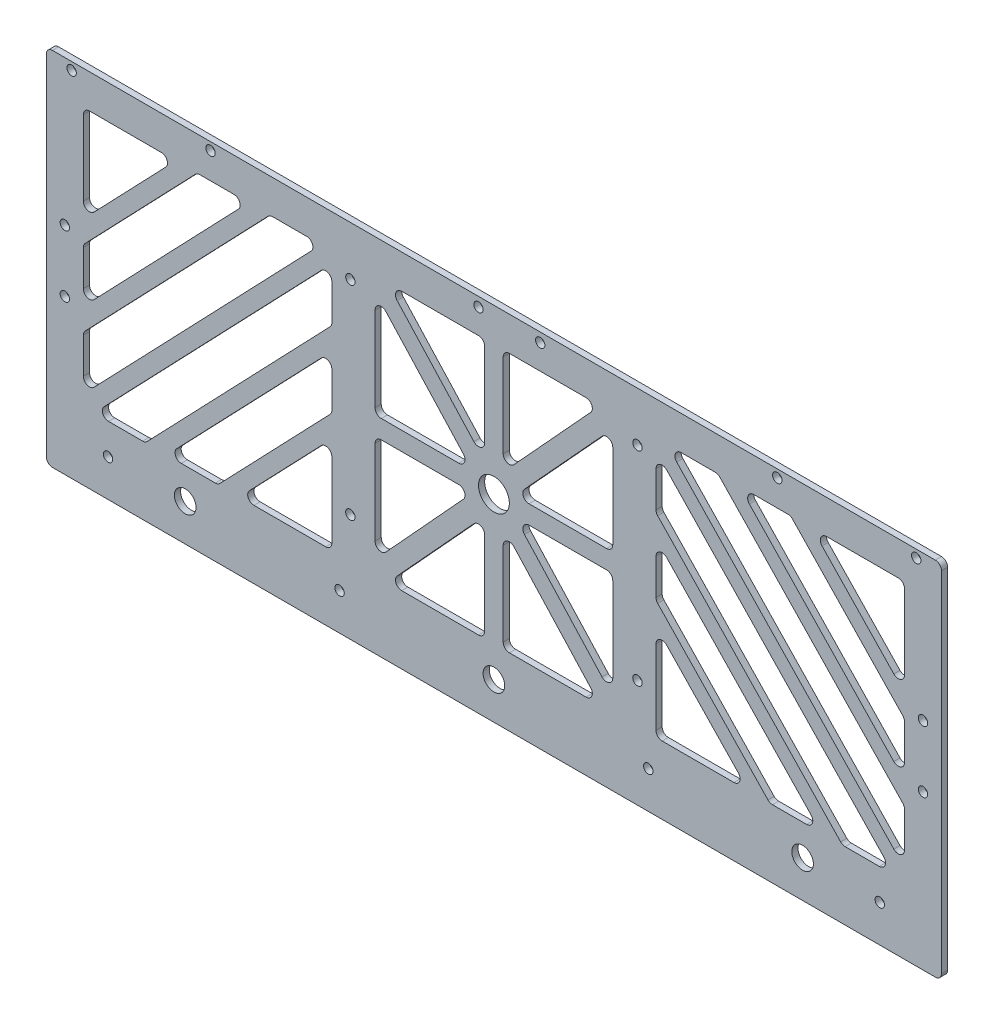
SolidWorks part; units mm, degrees
material "Thornel Mat VMA"
ref_plane "前视基准面" through (0, 0, 0) normal (0, 0, 1) x (1, 0, 0)
ref_plane "上视基准面" through (0, 0, 0) normal (0, 1, 0) x (1, 0, 0)
ref_plane "右视基准面" through (0, 0, 0) normal (1, 0, 0) x (0, 0, -1)
sketch "草图1" plane through (0, 0, 0) normal (0, 0, 1) x (1, 0, 0)
  line L1 (-145, -58.5) -> (145, -58.5)
  line L2 (-145, -58.5) -> (-145, 58.5)
  line L3 (-145, 58.5) -> (145, 58.5)
  line L4 (145, -58.5) -> (145, 58.5)
  line L5 (0, 58.5) -> (0, -58.5) construction
  line L6 (-145, 0) -> (145, 0) construction
  point P0 (0, 0)
  dimension "D1" = 290
  dimension "D2" = 117
extrude "凸台-拉伸1" add sketch "草图1" along normal mid plane 2
sketch "草图2" plane through (0, 0, -1) normal (0, 0, -1) x (-1, 0, 0)
  circle A0 centre (136.8, 56) radius 1.25 construction
  circle A1 centre (91.8, 56) radius 1.25 construction
  circle A2 centre (136.8, 56) radius 1.25 construction
  circle A3 centre (91.8, 56) radius 1.25 construction
  circle A4 centre (91.8, 56) radius 1.525
  circle A5 centre (136.8, 56) radius 1.525
  dimension "D1" = 3.05
extrude "切除-拉伸1" cut sketch "草图2" against normal blind 10
mirror "镜向1" about plane through (0, 0, 0) normal (1, 0, 0) of "切除-拉伸1"
sketch "草图3" plane through (0, 0, -1) normal (0, 0, -1) x (-1, 0, 0)
  circle A0 centre (100, -46.5) radius 3.5 construction
  circle A1 centre (0, -46.5) radius 3.5 construction
  circle A2 centre (-100, -46.5) radius 3.5 construction
  circle A3 centre (100, -46.5) radius 3.5
  circle A4 centre (0, -46.5) radius 3.5
  circle A5 centre (-100, -46.5) radius 3.5
extrude "切除-拉伸2" cut sketch "草图3" against normal blind 10
sketch "草图4" plane through (0, 0, -1) normal (0, 0, -1) x (-1, 0, 0)
  line L0 (-100, -46.5) -> (0, -46.5) construction
  line L1 (0, -46.5) -> (100, -46.5) construction
  line L2 (-100, -46.5) -> (-125, -46.5) construction
  line L3 (100, -46.5) -> (125, -46.5) construction
  circle A0 centre (-50, -46.5) radius 1.525
  circle A1 centre (50, -46.5) radius 1.525
  circle A2 centre (-125, -46.5) radius 1.525
  circle A3 centre (125, -46.5) radius 1.525
  dimension "D3" = 3.05
  dimension "D1" = 25
  dimension "D2" = 25
extrude "切除-拉伸3" cut sketch "草图4" against normal blind 10
sketch "草图5" plane through (0, 0, -1) normal (0, 0, -1) x (-1, 0, 0)
  circle A0 centre (139, -8.5) radius 1.25 construction
  circle A1 centre (139, 11.5) radius 1.25 construction
  circle A2 centre (139, -8.5) radius 1.25 construction
  circle A3 centre (139, 11.5) radius 1.25 construction
  circle A4 centre (139, 11.5) radius 1.525
  circle A5 centre (139, -8.5) radius 1.525
  dimension "D1" = 3.05
extrude "切除-拉伸4" cut sketch "草图5" against normal blind 10
mirror "镜向2" about plane through (0, 0, 0) normal (1, 0, 0) of "切除-拉伸4"
fillet "圆角1" radius 2 4 edges at (145, -58.5, 0) (-145, -58.5, 0) (-145, 58.5, 0) (145, 58.5, 0)
sketch "草图6" plane through (0, 0, -1) normal (0, 0, -1) x (-1, 0, 0)
  circle A0 centre (5, 55.5) radius 1.25 construction
  circle A1 centre (-15, 55.5) radius 1.25 construction
  circle A2 centre (5, 55.5) radius 1.25 construction
  circle A3 centre (-15, 55.5) radius 1.25 construction
  circle A4 centre (-15, 55.5) radius 1.5
  circle A5 centre (5, 55.5) radius 1.5
  dimension "D1" = 3
extrude "切除-拉伸5" cut sketch "草图6" against normal blind 10
sketch "草图7" plane through (0, 0, -1) normal (0, 0, -1) x (-1, 0, 0)
  circle A0 centre (-46.5, 42.5) radius 1.25 construction
  circle A1 centre (-46.5, -23.5) radius 1.25 construction
  circle A2 centre (-46.5, 42.5) radius 1.25 construction
  circle A3 centre (-46.5, -23.5) radius 1.25 construction
  circle A4 centre (-46.5, 42.5) radius 1.525
  circle A5 centre (-46.5, -23.5) radius 1.525
  dimension "D1" = 3.05
extrude "切除-拉伸6" cut sketch "草图7" against normal blind 10
mirror "镜向3" about plane through (0, 0, 0) normal (1, 0, 0) of "切除-拉伸6"
sketch "草图8" plane through (0, 0, -1) normal (0, 0, -1) x (-1, 0, 0)
  line L0 (-38.5, 47.5) -> (-38.5, -36.5)
  line L1 (-38.5, -36.5) -> (38.5, -36.5)
  line L2 (38.5, -36.5) -> (38.5, 47.5)
  line L3 (38.5, 47.5) -> (-38.5, 47.5)
  line L4 (0, 47.5) -> (0, -36.5) construction
  line L5 (-38.5, 47.5) -> (38.5, -36.5) construction
  line L6 (38.5, 47.5) -> (-38.5, -36.5) construction
  line L7 (-38.5, 5.5) -> (38.5, 5.5) construction
  line L8 (-40.7115, 45.4728) -> (36.2885, -38.5272)
  line L9 (-3, 47.5) -> (-3, -36.5)
  line L10 (36.2885, 49.5272) -> (-40.7115, -34.4728)
  line L11 (-38.5, 2.5) -> (38.5, 2.5)
  line L12 (-36.2885, 49.5272) -> (40.7115, -34.4728)
  line L13 (3, 47.5) -> (3, -36.5)
  line L14 (40.7115, 45.4728) -> (-36.2885, -38.5272)
  line L15 (-38.5, 8.5) -> (38.5, 8.5)
  circle A0 centre (0, -46.5) radius 3.5 construction
  circle A1 centre (-46.5, 42.5) radius 1.525 construction
  circle A2 centre (5, 55.5) radius 1.5 construction
  dimension "D2" = 8
  dimension "D1" = 10
  dimension "D3" = 8
  dimension "D4" = 3
  dimension "D5" = 3
extrude "切除-拉伸7" cut sketch "草图8" against normal blind 10 contours L8 L13 L1 | L9 L14 L1 | L11 L0 L10 | L0 L15 L8 | L3 L12 L9 | L3 L13 L10 | L14 L15 L2 | L11 L12 L2
fillet "圆角2" radius 2 24 edges at (-38.5, 2.5, 0) (-38.5, -32.0603, 0) (-6.8197, 2.5, 0) (-3, 13.2124, 0) (-3, 47.5, 0) (-34.4303, 47.5, 0) (-38.5, 8.5, 0) (-6.8197, 8.5, 0) (-38.5, 43.0603, 0) (6.8197, 8.5, 0) (38.5, 8.5, 0) (38.5, 43.0603, 0) (3, 13.2124, 0) (34.4303, 47.5, 0) (3, 47.5, 0) (6.8197, 2.5, 0) (38.5, -32.0603, 0) (38.5, 2.5, 0) (-34.4303, -36.5, 0) (-3, -36.5, 0) (-3, -2.2124, 0) (3, -2.2124, 0) (3, -36.5, 0) (34.4303, -36.5, 0)
sketch "草图9" plane through (0, 0, -1) normal (0, 0, -1) x (-1, 0, 0)
  line L0 (23.9331, 8.5) -> (23.9331, 2.5) construction
  line L1 (11.3662, 8.5) -> (36.5, 8.5) construction
  line L2 (11.3662, 2.5) -> (36.5, 2.5) construction
  line L3 (0, 5.5) -> (23.9331, 5.5) construction
  line L4 (0, 5.5) -> (0, 0) construction
  circle A0 centre (0, 5.5) radius 5
  dimension "D1" = 10
extrude "切除-拉伸8" cut sketch "草图9" against normal blind 10
sketch "草图10" plane through (0, 0, -1) normal (0, 0, -1) x (-1, 0, 0)
  line L0 (-5, 47.5) -> (-29.8838, 47.5) construction
  line L1 (-133, 47.5) -> (-52.5, 47.5)
  line L2 (-133, 47.5) -> (-133, -36.5)
  line L3 (-133, -36.5) -> (-52.5, -36.5)
  line L4 (-52.5, 47.5) -> (-52.5, -36.5)
  line L5 (-52.5, -5.2529) -> (-82.4452, -36.5)
  line L6 (-29.8838, -36.5) -> (-5, -36.5) construction
  line L7 (-133, -36.5) -> (-52.5, 47.5) construction
  line L8 (-129.5373, -36.5) -> (-52.5, 43.8868)
  line L9 (-133, -32.8868) -> (-55.9627, 47.5)
  line L10 (-112.9166, -36.5) -> (-52.5, 26.5434)
  line L11 (-52.5, 19.317) -> (-105.9912, -36.5)
  line L12 (-52.5, 1.9735) -> (-89.3705, -36.5)
  line L13 (-103.0548, 47.5) -> (-133, 16.2529)
  line L14 (-96.1295, 47.5) -> (-133, 9.0265)
  line L15 (-133, -15.5434) -> (-72.5834, 47.5)
  line L16 (-79.5088, 47.5) -> (-133, -8.317)
  line L17 (0, 0) -> (0, 58.5) construction
  line L18 (-143, 58.5) -> (143, 58.5) construction
  line L19 (133, -36.5) -> (52.5, 47.5) construction
  line L20 (79.5088, 47.5) -> (133, -8.317)
  line L21 (133, -15.5434) -> (72.5834, 47.5)
  line L22 (96.1295, 47.5) -> (133, 9.0265)
  line L23 (103.0548, 47.5) -> (133, 16.2529)
  line L24 (52.5, 1.9735) -> (89.3705, -36.5)
  line L25 (52.5, 19.317) -> (105.9912, -36.5)
  line L26 (112.9166, -36.5) -> (52.5, 26.5434)
  line L27 (133, -32.8868) -> (55.9627, 47.5)
  line L28 (129.5373, -36.5) -> (52.5, 43.8868)
  line L29 (52.5, -5.2529) -> (82.4452, -36.5)
  line L30 (52.5, 47.5) -> (52.5, -36.5)
  line L31 (133, -36.5) -> (52.5, -36.5)
  line L32 (133, 47.5) -> (133, -36.5)
  line L33 (133, 47.5) -> (52.5, 47.5)
  circle A0 centre (-46.5, -23.5) radius 1.525 construction
  circle A1 centre (-139, 11.5) radius 1.525 construction
  dimension "D1" = 6
  dimension "D2" = 6
  dimension "D3" = 5
  dimension "D4" = 12
  dimension "D5" = 5
  dimension "D6" = 12
  dimension "D7" = 5
  dimension "D8" = 12
  dimension "D9" = 5
  dimension "D10" = 12
  dimension "D11" = 5
extrude "切除-拉伸9" cut sketch "草图10" against normal blind 10 contours L4 L5 L3 | L12 L4 L11 L3 | L3 L10 L4 L8 | L15 L2 L9 L1 | L16 L1 L14 L2 | L13 L1 L2 | L31 L29 L30 | L31 L25 L30 L24 | L31 L28 L30 L26 | L21 L33 L27 L32 | L22 L33 L20 L32 | L32 L33 L23
fillet "圆角3" radius 2 44 edges at (133, 16.2529, 0) (133, 47.5, 0) (103.0548, 47.5, 0) (-112.9166, -36.5, 0) (-52.5, 26.5434, 0) (-52.5, 43.8868, 0) (-129.5373, -36.5, 0) (105.9912, -36.5, 0) (52.5, 19.317, 0) (52.5, 1.9735, 0) (72.5834, 47.5, 0) (55.9627, 47.5, 0) (133, -32.8868, 0) (133, -15.5434, 0) (-133, 9.0265, 0) (-133, -8.317, 0) (-79.5088, 47.5, 0) (-96.1295, 47.5, 0) (82.4452, -36.5, 0) (52.5, -5.2529, 0) (-133, -32.8868, 0) (-55.9627, 47.5, 0) (-72.5834, 47.5, 0) (-133, -15.5434, 0) (-133, 16.2529, 0) (-103.0548, 47.5, 0) (-133, 47.5, 0) (133, -8.317, 0) (133, 9.0265, 0) (96.1295, 47.5, 0) (79.5088, 47.5, 0) (52.5, 43.8868, 0) (52.5, 26.5434, 0) (112.9166, -36.5, 0) (129.5373, -36.5, 0) (-89.3705, -36.5, 0) (-52.5, 1.9735, 0) (-52.5, 19.317, 0) (-105.9912, -36.5, 0) (-52.5, -36.5, 0) (-52.5, -5.2529, 0) (-82.4452, -36.5, 0) (89.3705, -36.5, 0) (52.5, -36.5, 0)
equation "\"D5@草图10\"=\"D3@草图10\""
equation "\"D6@草图10\"=\"D4@草图10\""
equation "\"D7@草图10\"=\"D3@草图10\""
equation "\"D8@草图10\"=\"D4@草图10\""
equation "\"D9@草图10\"=\"D3@草图10\""
equation "\"D10@草图10\"=\"D4@草图10\""
equation "\"D11@草图10\"=\"D3@草图10\""
